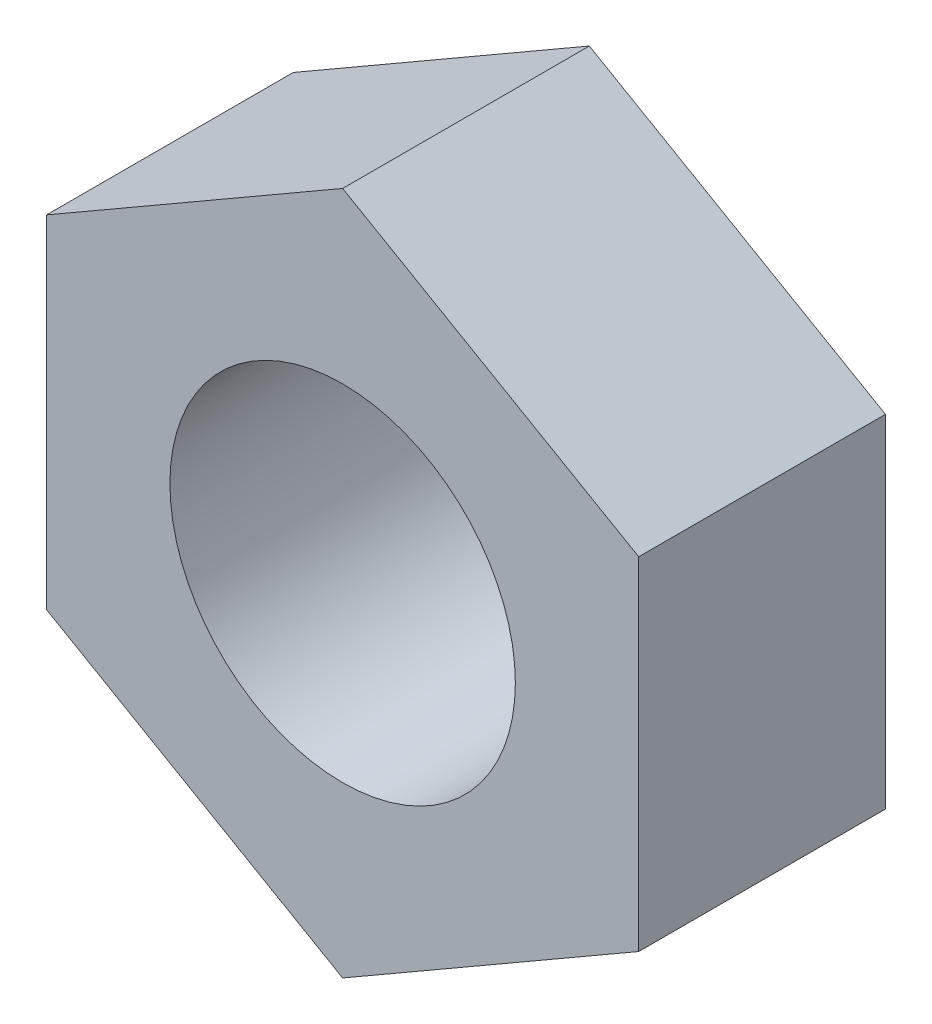
SolidWorks part; units mm, degrees
material "PBT General Purpose"
ref_plane "Front Plane" through (0, 0, 0) normal (0, 0, 1) x (1, 0, 0)
ref_plane "Top Plane" through (0, 0, 0) normal (0, 1, 0) x (1, 0, 0)
ref_plane "Right Plane" through (0, 0, 0) normal (1, 0, 0) x (0, 0, -1)
sketch "Sketch1" plane through (0, 0, 0) normal (0, 0, 1) x (1, 0, 0)
  line L1 (0, 13.8564) -> (-12, 6.9282)
  line L2 (-12, 6.9282) -> (-12, -6.9282)
  line L3 (-12, -6.9282) -> (0, -13.8564)
  line L4 (0, -13.8564) -> (12, -6.9282)
  line L5 (12, -6.9282) -> (12, 6.9282)
  line L6 (12, 6.9282) -> (0, 13.8564)
  circle A0 centre (0, 0) radius 7
  circle A1 centre (0, 0) radius 12 construction
  point P4 (0, 0)
  point P12 (3.7907, 2.4162)
  point P13 (0, 0)
  point P14 (0, 11.2162)
  point P15 (0, 0)
  dimension "D1" = 14
  dimension "D2" = 24
extrude "Boss-Extrude1" add sketch "Sketch1" along normal mid plane 10
